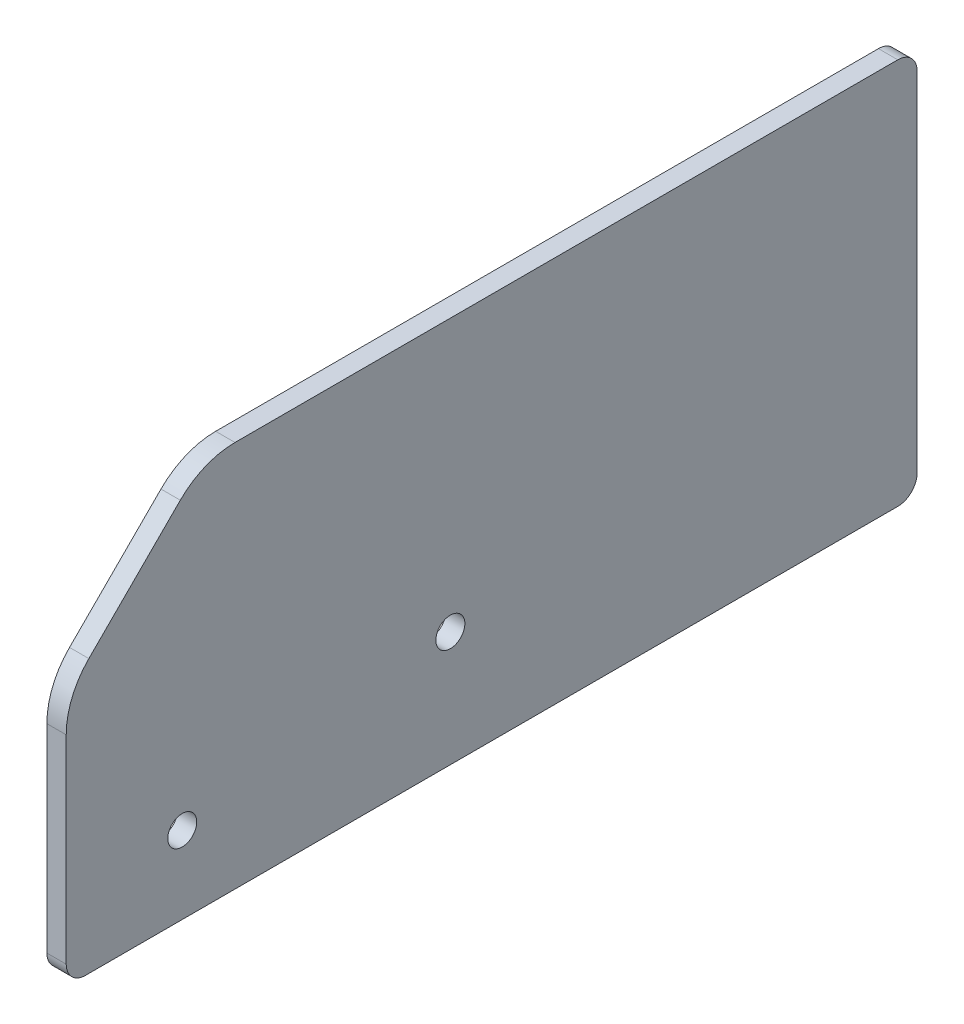
SolidWorks part; units mm, degrees
material "Thornel Mat VMA"
ref_plane "Front Plane" through (0, 0, 0) normal (0, 0, 1) x (1, 0, 0)
ref_plane "Top Plane" through (0, 0, 0) normal (0, 1, 0) x (1, 0, 0)
ref_plane "Right Plane" through (0, 0, 0) normal (1, 0, 0) x (0, 0, -1)
sketch "Sketch1" plane through (0, 0, 0) normal (1, 0, 0) x (0, 0, -1)
  line L0 (38.1, 25.4) -> (38.1, 0) construction
  line L1 (6.35, 0) -> (273.05, 0)
  line L2 (0, 6.35) -> (0, 71.5777)
  line L3 (55.4223, 127) -> (273.05, 127)
  line L4 (279.4, 6.35) -> (279.4, 120.65)
  line L5 (38.1, 25.4) -> (0, 25.4) construction
  line L6 (38.1, 25.4) -> (127, 25.4) construction
  line L7 (7.4395, 89.5382) -> (37.4618, 119.5605)
  line L8 (126.1348, 37.7725) -> (38.1, 25.4) construction
  line L9 (38.1, 25.4) -> (126.1348, 13.0275) construction
  line L10 (123.5562, 49.9042) -> (38.1, 25.4) construction
  circle A0 centre (38.1, 25.4) radius 4.7625
  circle A1 centre (38.1, 25.4) radius 88.9 construction
  circle A2 centre (126.1348, 13.0275) radius 4.7625 construction
  circle A3 centre (127, 25.4) radius 4.7625 construction
  circle A4 centre (126.1348, 37.7725) radius 4.7625
  circle A5 centre (123.5562, 49.9042) radius 4.7625 construction
  circle A6 centre (38.1, 25.4) radius 93.6625 construction
  arc A7 (273.05, 0) -> (279.4, 6.35) centre (273.05, 6.35) ccw
  arc A8 (273.05, 127) -> (279.4, 120.65) centre (273.05, 120.65) cw
  arc A9 (6.35, 0) -> (0, 6.35) centre (6.35, 6.35) cw
  arc A10 (37.4618, 119.5605) -> (55.4223, 127) centre (55.4223, 101.6) cw
  arc A11 (7.4395, 89.5382) -> (0, 71.5777) centre (25.4, 71.5777) ccw
  point P20 (44.9013, 127)
  point P23 (279.4, 0)
  point P28 (0, 0)
  point P33 (0, 82.0987)
  dimension "D3" = 9.525
  dimension "D6" = 177.8
  dimension "D7" = 4.7625
  dimension "D11" = 6.35
  dimension "D14" = 25.4
  dimension "D1" = 279.4
  dimension "D2" = 127
  dimension "D4" = 25.4
  dimension "D5" = 38.1
  dimension "D8" = 8
  dimension "D9" = 8
  dimension "D10" = 8
  dimension "D12" = 135
  dimension "D13" = 63.5
extrude "Boss-Extrude1" add sketch "Sketch1" along normal blind 6.35
